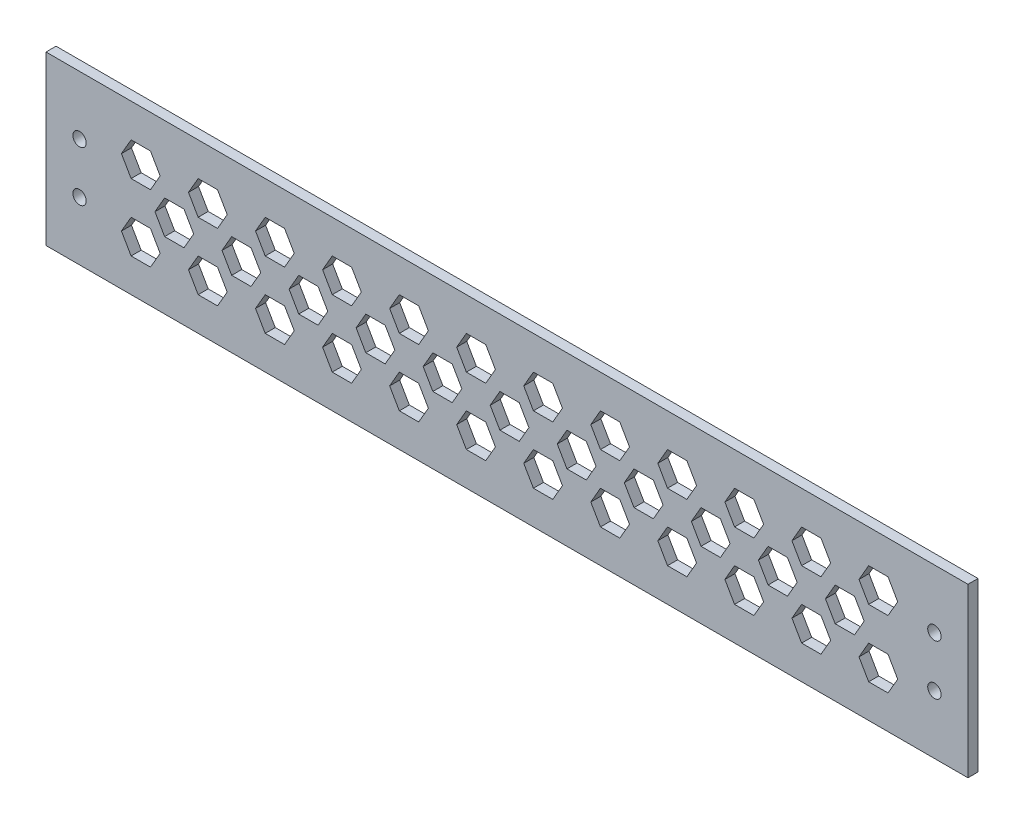
SolidWorks part; units mm, degrees
material "Thornel Mat VMA"
ref_plane "前视基准面" through (0, 0, 0) normal (0, 0, 1) x (1, 0, 0)
ref_plane "上视基准面" through (0, 0, 0) normal (0, 1, 0) x (1, 0, 0)
ref_plane "右视基准面" through (0, 0, 0) normal (1, 0, 0) x (0, 0, -1)
sketch "Sketch1" plane through (0, 0, 0) normal (0, 0, 1) x (1, 0, 0)
  line L0 (137.5, 50) -> (137.5, 0) construction
  line L1 (0, 0) -> (275, 0)
  line L2 (0, 0) -> (0, 50)
  line L3 (0, 50) -> (275, 50)
  line L4 (275, 0) -> (275, 50)
  circle A0 centre (10, 32.5) radius 2
  circle A1 centre (10, 17.5) radius 2
  circle A2 centre (265, 17.5) radius 2
  circle A3 centre (265, 32.5) radius 2
  dimension "D6" = 15
  dimension "D7" = 4
  dimension "D8" = 4
  dimension "D1" = 50
  dimension "D2" = 275
  dimension "D3" = 10
  dimension "D4" = 10
  dimension "D5" = 17.5
extrude "Boss-Extrude1" add sketch "Sketch1" along normal blind 3
sketch "Sketch3" plane through (0, 0, 3) normal (0, 0, 1) x (1, 0, 0)
  line L0 (275, 50) -> (0, 50) construction
  line L1 (34.047, 35) -> (31.1603, 40)
  line L2 (31.1603, 40) -> (25.3868, 40)
  line L3 (25.3868, 40) -> (22.5, 35)
  line L4 (22.5, 35) -> (25.3868, 30)
  line L5 (25.3868, 30) -> (31.1603, 30)
  line L6 (31.1603, 30) -> (34.047, 35)
  line L7 (0, 50) -> (0, 0) construction
  circle A0 centre (28.2735, 35) radius 5 construction
  dimension "D1" = 10
  dimension "D2" = 10
  dimension "D3" = 22.5
extrude "Cut-Extrude2" cut sketch "Sketch3" against normal blind 3
pattern_linear "LPattern1" count 12 spacing 20 along (1, 0, 0) of "Cut-Extrude2"
sketch "Sketch5" plane through (0, 0, 3) normal (0, 0, 1) x (1, 0, 0)
  line L0 (22.5, 35) -> (54.047, 35) construction
  line L2 (32.5, 25) -> (35.3868, 20)
  line L3 (35.3868, 20) -> (41.1603, 20)
  line L4 (41.1603, 20) -> (44.047, 25)
  line L5 (44.047, 25) -> (41.1603, 30)
  line L6 (41.1603, 30) -> (35.3868, 30)
  line L7 (35.3868, 30) -> (32.5, 25)
  line L8 (51.1603, 40) -> (45.3868, 40) construction
  circle A0 centre (38.2735, 25) radius 5 construction
  point P5 (48.2735, 40)
  dimension "D1" = 10
  dimension "D2" = 10
  dimension "D3" = 10
extrude "Cut-Extrude3" cut sketch "Sketch5" against normal blind 3
pattern_linear "LPattern2" count 11 spacing 20 along (1, 0, 0) of "Cut-Extrude3"
sketch "Sketch6" plane through (0, 0, 3) normal (0, 0, 1) x (1, 0, 0)
  line L0 (28.2735, 40) -> (28.2735, 4.7416) construction
  line L1 (31.1603, 40) -> (25.3868, 40) construction
  line L2 (35.3868, 20) -> (41.1603, 20) construction
  line L3 (34.047, 15) -> (31.1603, 20)
  line L4 (31.1603, 20) -> (25.3868, 20)
  line L5 (25.3868, 20) -> (22.5, 15)
  line L6 (22.5, 15) -> (25.3868, 10)
  line L7 (25.3868, 10) -> (31.1603, 10)
  line L8 (31.1603, 10) -> (34.047, 15)
  circle A0 centre (28.2735, 15) radius 5 construction
  dimension "D1" = 10
  dimension "D2" = 5
extrude "Cut-Extrude4" cut sketch "Sketch6" against normal blind 3
pattern_linear "LPattern3" count 12 spacing 20 along (1, 0, 0) of "Cut-Extrude4"
